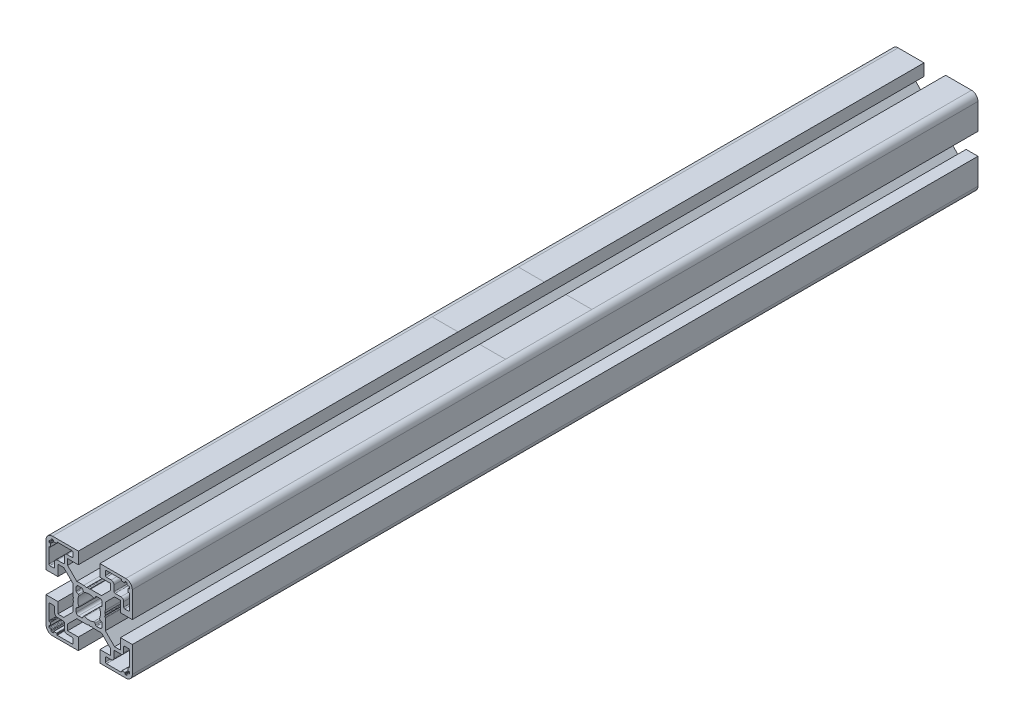
SolidWorks part; units mm, degrees
material "6063-T5"
ref_plane "Front Plane" through (0, 0, 0) normal (0, 0, 1) x (1, 0, 0)
ref_plane "Top Plane" through (0, 0, 0) normal (0, 1, 0) x (1, 0, 0)
ref_plane "Right Plane" through (0, 0, 0) normal (1, 0, 0) x (0, 0, -1)
ref_plane "Plan1" through (0, 0, 50) normal (0, 0, 1) x (1, 0, 0)
sketch "Esquisse1" plane through (0, 0, 50) normal (0, 0, 1) x (1, 0, 0)
  line L0 (-11.2645, -4.6769) -> (-11.2645, 2.1231)
  line L1 (-10.7645, 2.6231) -> (-9.0645, 2.6231)
  line L2 (-8.5645, 2.1231) -> (-8.5645, -0.0769)
  line L3 (-7.2645, -1.3769) -> (-4.5645, -1.3769)
  line L4 (-4.0645, -1.8769) -> (-4.0645, -4.5769)
  line L5 (-2.7645, -5.8769) -> (-0.5645, -5.8769)
  line L6 (-0.0645, -6.3769) -> (-0.0645, -8.0769)
  line L7 (-0.5645, -8.5769) -> (-7.3645, -8.5769)
  line L8 (-7.5645, -8.3769) -> (-7.5645, -8.0769)
  line L9 (-7.7645, -7.8769) -> (-8.9645, -7.8769)
  line L10 (-9.1645, -8.0769) -> (-9.1645, -8.3769)
  line L11 (-9.3645, -8.5769) -> (-9.8645, -8.5769)
  line L12 (-10.1645, -8.2769) -> (-10.1645, -7.7769)
  line L13 (-10.4645, -7.4769) -> (-10.9645, -7.4769)
  line L14 (-11.2645, -7.1769) -> (-11.2645, -6.6769)
  line L15 (-11.0645, -6.4769) -> (-10.7645, -6.4769)
  line L16 (-10.5645, -6.2769) -> (-10.5645, -5.0769)
  line L17 (-10.7645, -4.8769) -> (-11.0645, -4.8769)
  line L18 (14.9355, -8.0769) -> (14.9355, -6.3769)
  line L19 (15.4355, -5.8769) -> (17.6355, -5.8769)
  line L20 (18.9355, -4.5769) -> (18.9355, -1.8769)
  line L21 (19.4355, -1.3769) -> (22.1355, -1.3769)
  line L22 (23.4355, -0.0769) -> (23.4355, 2.1231)
  line L23 (23.9355, 2.6231) -> (25.6355, 2.6231)
  line L24 (26.1355, 2.1231) -> (26.1355, -4.6769)
  line L25 (25.9355, -4.8769) -> (25.6355, -4.8769)
  line L26 (25.4355, -5.0769) -> (25.4355, -6.2769)
  line L27 (25.6355, -6.4769) -> (25.9355, -6.4769)
  line L28 (26.1355, -6.6769) -> (26.1355, -7.1769)
  line L29 (25.8355, -7.4769) -> (25.3355, -7.4769)
  line L30 (25.0355, -7.7769) -> (25.0355, -8.2769)
  line L31 (24.7355, -8.5769) -> (24.2355, -8.5769)
  line L32 (24.0355, -8.3769) -> (24.0355, -8.0769)
  line L33 (23.8355, -7.8769) -> (22.6355, -7.8769)
  line L34 (22.4355, -8.0769) -> (22.4355, -8.3769)
  line L35 (22.2355, -8.5769) -> (15.4355, -8.5769)
  line L36 (-12.5645, 27.1231) -> (-12.5645, 15.1231)
  line L37 (-12.5645, 15.1231) -> (-7.0645, 15.1231)
  line L38 (-7.0645, 15.1231) -> (-7.0645, 20.1231)
  line L39 (-7.0645, 20.1231) -> (-4.3322, 20.1231)
  line L40 (-4.3322, 20.1231) -> (-0.0645, 15.8553)
  line L41 (-0.0645, 15.8553) -> (-0.0645, 10.7767)
  line L42 (0.0025, 10.5267) -> (0.2355, 10.1231)
  line L43 (0.2355, 10.1231) -> (0.0025, 9.7195)
  line L44 (0.0025, 9.2195) -> (0.1846, 8.9042)
  line L45 (0.1846, 8.9042) -> (-0.0645, 7.6231)
  line L46 (-0.0645, 7.6231) -> (-0.0645, 4.3908)
  line L47 (-0.0645, 4.3908) -> (-4.3322, 0.1231)
  line L48 (-4.3322, 0.1231) -> (-7.0645, 0.1231)
  line L49 (-7.0645, 0.1231) -> (-7.0645, 5.1231)
  line L50 (-7.0645, 5.1231) -> (-12.5645, 5.1231)
  line L51 (-12.5645, 5.1231) -> (-12.5645, -6.8769)
  line L52 (-9.5645, -9.8769) -> (2.4355, -9.8769)
  line L53 (2.4355, -9.8769) -> (2.4355, -4.3769)
  line L54 (2.4355, -4.3769) -> (-2.5645, -4.3769)
  line L55 (-2.5645, -4.3769) -> (-2.5645, -1.6447)
  line L56 (-2.5645, -1.6447) -> (1.7033, 2.6231)
  line L57 (1.7033, 2.6231) -> (6.7819, 2.6231)
  line L58 (7.0319, 2.6901) -> (7.4355, 2.9231)
  line L59 (7.4355, 2.9231) -> (7.8391, 2.6901)
  line L60 (8.3391, 2.6901) -> (8.6544, 2.8721)
  line L61 (8.6544, 2.8721) -> (9.9355, 2.6231)
  line L62 (9.9355, 2.6231) -> (13.1678, 2.6231)
  line L63 (13.1678, 2.6231) -> (17.4355, -1.6447)
  line L64 (17.4355, -1.6447) -> (17.4355, -4.3769)
  line L65 (17.4355, -4.3769) -> (12.4355, -4.3769)
  line L66 (12.4355, -4.3769) -> (12.4355, -9.8769)
  line L67 (12.4355, -9.8769) -> (24.4355, -9.8769)
  line L68 (27.4355, -6.8769) -> (27.4355, 5.1231)
  line L69 (27.4355, 5.1231) -> (21.9355, 5.1231)
  line L70 (21.9355, 5.1231) -> (21.9355, 0.1231)
  line L71 (21.9355, 0.1231) -> (19.2033, 0.1231)
  line L72 (19.2033, 0.1231) -> (14.9355, 4.3908)
  line L73 (14.9355, 4.3908) -> (14.9355, 9.4695)
  line L74 (14.8686, 9.7195) -> (14.6355, 10.1231)
  line L75 (14.6355, 10.1231) -> (14.8686, 10.5267)
  line L76 (14.8686, 11.0267) -> (14.6865, 11.342)
  line L77 (14.6865, 11.342) -> (14.9355, 12.6231)
  line L78 (14.9355, 12.6231) -> (14.9355, 15.8553)
  line L79 (14.9355, 15.8553) -> (19.2033, 20.1231)
  line L80 (19.2033, 20.1231) -> (21.9355, 20.1231)
  line L81 (21.9355, 20.1231) -> (21.9355, 15.1231)
  line L82 (21.9355, 15.1231) -> (27.4355, 15.1231)
  line L83 (27.4355, 15.1231) -> (27.4355, 27.1231)
  line L84 (24.4355, 30.1231) -> (12.4355, 30.1231)
  line L85 (12.4355, 30.1231) -> (12.4355, 24.6231)
  line L86 (12.4355, 24.6231) -> (17.4355, 24.6231)
  line L87 (17.4355, 24.6231) -> (17.4355, 21.8908)
  line L88 (17.4355, 21.8908) -> (13.1678, 17.6231)
  line L89 (13.1678, 17.6231) -> (8.0891, 17.6231)
  line L90 (7.8391, 17.5561) -> (7.4355, 17.3231)
  line L91 (7.4355, 17.3231) -> (7.0319, 17.5561)
  line L92 (6.5319, 17.5561) -> (6.2167, 17.3741)
  line L93 (6.2167, 17.3741) -> (4.9355, 17.6231)
  line L94 (4.9355, 17.6231) -> (1.7033, 17.6231)
  line L95 (1.7033, 17.6231) -> (-2.5645, 21.8908)
  line L96 (-2.5645, 21.8908) -> (-2.5645, 24.6231)
  line L97 (-2.5645, 24.6231) -> (2.4355, 24.6231)
  line L98 (2.4355, 24.6231) -> (2.4355, 30.1231)
  line L99 (2.4355, 30.1231) -> (-9.5645, 30.1231)
  line L100 (14.9355, 26.6231) -> (14.9355, 28.3231)
  line L101 (15.4355, 28.8231) -> (22.2355, 28.8231)
  line L102 (22.4355, 28.6231) -> (22.4355, 28.3231)
  line L103 (22.6355, 28.1231) -> (23.8355, 28.1231)
  line L104 (24.0355, 28.3231) -> (24.0355, 28.6231)
  line L105 (24.2355, 28.8231) -> (24.7355, 28.8231)
  line L106 (25.0355, 28.5231) -> (25.0355, 28.0231)
  line L107 (25.3355, 27.7231) -> (25.8355, 27.7231)
  line L108 (26.1355, 27.4231) -> (26.1355, 26.9231)
  line L109 (25.9355, 26.7231) -> (25.6355, 26.7231)
  line L110 (25.4355, 26.5231) -> (25.4355, 25.3231)
  line L111 (25.6355, 25.1231) -> (25.9355, 25.1231)
  line L112 (26.1355, 24.9231) -> (26.1355, 18.1231)
  line L113 (25.6355, 17.6231) -> (23.9355, 17.6231)
  line L114 (23.4355, 18.1231) -> (23.4355, 20.3231)
  line L115 (22.1355, 21.6231) -> (19.4355, 21.6231)
  line L116 (18.9355, 22.1231) -> (18.9355, 24.8231)
  line L117 (17.6355, 26.1231) -> (15.4355, 26.1231)
  line L118 (-11.2645, 18.1231) -> (-11.2645, 24.9231)
  line L119 (-11.0645, 25.1231) -> (-10.7645, 25.1231)
  line L120 (-10.5645, 25.3231) -> (-10.5645, 26.5231)
  line L121 (-10.7645, 26.7231) -> (-11.0645, 26.7231)
  line L122 (-11.2645, 26.9231) -> (-11.2645, 27.4231)
  line L123 (-10.9645, 27.7231) -> (-10.4645, 27.7231)
  line L124 (-10.1645, 28.0231) -> (-10.1645, 28.5231)
  line L125 (-9.8645, 28.8231) -> (-9.3645, 28.8231)
  line L126 (-9.1645, 28.6231) -> (-9.1645, 28.3231)
  line L127 (-8.9645, 28.1231) -> (-7.7645, 28.1231)
  line L128 (-7.5645, 28.3231) -> (-7.5645, 28.6231)
  line L129 (-7.3645, 28.8231) -> (-0.5645, 28.8231)
  line L130 (-0.0645, 28.3231) -> (-0.0645, 26.6231)
  line L131 (-0.5645, 26.1231) -> (-2.7645, 26.1231)
  line L132 (-4.0645, 24.8231) -> (-4.0645, 22.1231)
  line L133 (-4.5645, 21.6231) -> (-7.2645, 21.6231)
  line L134 (-8.5645, 20.3231) -> (-8.5645, 18.1231)
  line L135 (-9.0645, 17.6231) -> (-10.7645, 17.6231)
  line L136 (10.9262, 16.1231) -> (12.4355, 16.1231)
  line L137 (13.4355, 15.1231) -> (13.4355, 13.6138)
  line L138 (13.1703, 13.1723) -> (12.4933, 12.8123)
  line L139 (12.4933, 7.4338) -> (13.1703, 7.0739)
  line L140 (13.4355, 6.6324) -> (13.4355, 5.1231)
  line L141 (12.4355, 4.1231) -> (10.9262, 4.1231)
  line L142 (10.4848, 4.3883) -> (10.1248, 5.0654)
  line L143 (4.7463, 5.0654) -> (4.3863, 4.3883)
  line L144 (3.9449, 4.1231) -> (2.4355, 4.1231)
  line L145 (1.4355, 5.1231) -> (1.4355, 6.6324)
  line L146 (1.7008, 7.0739) -> (2.3778, 7.4338)
  line L147 (2.3778, 12.8123) -> (1.7008, 13.1723)
  line L148 (1.4355, 13.6138) -> (1.4355, 15.1231)
  line L149 (2.4355, 16.1231) -> (3.9449, 16.1231)
  line L150 (4.3863, 15.8578) -> (4.7463, 15.1808)
  line L151 (10.1248, 15.1808) -> (10.4848, 15.8578)
  arc A0 (-11.2645, 2.1231) -> (-10.7645, 2.6231) centre (-10.7645, 2.1231) cw
  arc A1 (-9.0645, 2.6231) -> (-8.5645, 2.1231) centre (-9.0645, 2.1231) cw
  arc A2 (-8.5645, -0.0769) -> (-7.2645, -1.3769) centre (-7.2645, -0.0769) ccw
  arc A3 (-4.5645, -1.3769) -> (-4.0645, -1.8769) centre (-4.5645, -1.8769) cw
  arc A4 (-4.0645, -4.5769) -> (-2.7645, -5.8769) centre (-2.7645, -4.5769) ccw
  arc A5 (-0.5645, -5.8769) -> (-0.0645, -6.3769) centre (-0.5645, -6.3769) cw
  arc A6 (-0.0645, -8.0769) -> (-0.5645, -8.5769) centre (-0.5645, -8.0769) cw
  arc A7 (-7.3645, -8.5769) -> (-7.5645, -8.3769) centre (-7.3645, -8.3769) cw
  arc A8 (-7.5645, -8.0769) -> (-7.7645, -7.8769) centre (-7.7645, -8.0769) ccw
  arc A9 (-8.9645, -7.8769) -> (-9.1645, -8.0769) centre (-8.9645, -8.0769) ccw
  arc A10 (-9.1645, -8.3769) -> (-9.3645, -8.5769) centre (-9.3645, -8.3769) cw
  arc A11 (-9.8645, -8.5769) -> (-10.1645, -8.2769) centre (-9.8645, -8.2769) cw
  arc A12 (-10.1645, -7.7769) -> (-10.4645, -7.4769) centre (-10.4645, -7.7769) ccw
  arc A13 (-10.9645, -7.4769) -> (-11.2645, -7.1769) centre (-10.9645, -7.1769) cw
  arc A14 (-11.2645, -6.6769) -> (-11.0645, -6.4769) centre (-11.0645, -6.6769) cw
  arc A15 (-10.7645, -6.4769) -> (-10.5645, -6.2769) centre (-10.7645, -6.2769) ccw
  arc A16 (-10.5645, -5.0769) -> (-10.7645, -4.8769) centre (-10.7645, -5.0769) ccw
  arc A17 (-11.0645, -4.8769) -> (-11.2645, -4.6769) centre (-11.0645, -4.6769) cw
  arc A18 (14.9355, -6.3769) -> (15.4355, -5.8769) centre (15.4355, -6.3769) cw
  arc A19 (17.6355, -5.8769) -> (18.9355, -4.5769) centre (17.6355, -4.5769) ccw
  arc A20 (18.9355, -1.8769) -> (19.4355, -1.3769) centre (19.4355, -1.8769) cw
  arc A21 (22.1355, -1.3769) -> (23.4355, -0.0769) centre (22.1355, -0.0769) ccw
  arc A22 (23.4355, 2.1231) -> (23.9355, 2.6231) centre (23.9355, 2.1231) cw
  arc A23 (25.6355, 2.6231) -> (26.1355, 2.1231) centre (25.6355, 2.1231) cw
  arc A24 (26.1355, -4.6769) -> (25.9355, -4.8769) centre (25.9355, -4.6769) cw
  arc A25 (25.6355, -4.8769) -> (25.4355, -5.0769) centre (25.6355, -5.0769) ccw
  arc A26 (25.4355, -6.2769) -> (25.6355, -6.4769) centre (25.6355, -6.2769) ccw
  arc A27 (25.9355, -6.4769) -> (26.1355, -6.6769) centre (25.9355, -6.6769) cw
  arc A28 (26.1355, -7.1769) -> (25.8355, -7.4769) centre (25.8355, -7.1769) cw
  arc A29 (25.3355, -7.4769) -> (25.0355, -7.7769) centre (25.3355, -7.7769) ccw
  arc A30 (25.0355, -8.2769) -> (24.7355, -8.5769) centre (24.7355, -8.2769) cw
  arc A31 (24.2355, -8.5769) -> (24.0355, -8.3769) centre (24.2355, -8.3769) cw
  arc A32 (24.0355, -8.0769) -> (23.8355, -7.8769) centre (23.8355, -8.0769) ccw
  arc A33 (22.6355, -7.8769) -> (22.4355, -8.0769) centre (22.6355, -8.0769) ccw
  arc A34 (22.4355, -8.3769) -> (22.2355, -8.5769) centre (22.2355, -8.3769) cw
  arc A35 (15.4355, -8.5769) -> (14.9355, -8.0769) centre (15.4355, -8.0769) cw
  arc A36 (-9.5645, 30.1231) -> (-12.5645, 27.1231) centre (-9.5645, 27.1231) ccw
  arc A37 (-0.0645, 10.7767) -> (0.0025, 10.5267) centre (0.4355, 10.7767) ccw
  arc A38 (0.0025, 9.7195) -> (0.0025, 9.2195) centre (0.4355, 9.4695) ccw
  arc A39 (-12.5645, -6.8769) -> (-9.5645, -9.8769) centre (-9.5645, -6.8769) ccw
  arc A40 (6.7819, 2.6231) -> (7.0319, 2.6901) centre (6.7819, 3.1231) ccw
  arc A41 (7.8391, 2.6901) -> (8.3391, 2.6901) centre (8.0891, 3.1231) ccw
  arc A42 (24.4355, -9.8769) -> (27.4355, -6.8769) centre (24.4355, -6.8769) ccw
  arc A43 (14.9355, 9.4695) -> (14.8686, 9.7195) centre (14.4355, 9.4695) ccw
  arc A44 (14.8686, 10.5267) -> (14.8686, 11.0267) centre (14.4355, 10.7767) ccw
  arc A45 (27.4355, 27.1231) -> (24.4355, 30.1231) centre (24.4355, 27.1231) ccw
  arc A46 (8.0891, 17.6231) -> (7.8391, 17.5561) centre (8.0891, 17.1231) ccw
  arc A47 (7.0319, 17.5561) -> (6.5319, 17.5561) centre (6.7819, 17.1231) ccw
  arc A48 (14.9355, 28.3231) -> (15.4355, 28.8231) centre (15.4355, 28.3231) cw
  arc A49 (22.2355, 28.8231) -> (22.4355, 28.6231) centre (22.2355, 28.6231) cw
  arc A50 (22.4355, 28.3231) -> (22.6355, 28.1231) centre (22.6355, 28.3231) ccw
  arc A51 (23.8355, 28.1231) -> (24.0355, 28.3231) centre (23.8355, 28.3231) ccw
  arc A52 (24.0355, 28.6231) -> (24.2355, 28.8231) centre (24.2355, 28.6231) cw
  arc A53 (24.7355, 28.8231) -> (25.0355, 28.5231) centre (24.7355, 28.5231) cw
  arc A54 (25.0355, 28.0231) -> (25.3355, 27.7231) centre (25.3355, 28.0231) ccw
  arc A55 (25.8355, 27.7231) -> (26.1355, 27.4231) centre (25.8355, 27.4231) cw
  arc A56 (26.1355, 26.9231) -> (25.9355, 26.7231) centre (25.9355, 26.9231) cw
  arc A57 (25.6355, 26.7231) -> (25.4355, 26.5231) centre (25.6355, 26.5231) ccw
  arc A58 (25.4355, 25.3231) -> (25.6355, 25.1231) centre (25.6355, 25.3231) ccw
  arc A59 (25.9355, 25.1231) -> (26.1355, 24.9231) centre (25.9355, 24.9231) cw
  arc A60 (26.1355, 18.1231) -> (25.6355, 17.6231) centre (25.6355, 18.1231) cw
  arc A61 (23.9355, 17.6231) -> (23.4355, 18.1231) centre (23.9355, 18.1231) cw
  arc A62 (23.4355, 20.3231) -> (22.1355, 21.6231) centre (22.1355, 20.3231) ccw
  arc A63 (19.4355, 21.6231) -> (18.9355, 22.1231) centre (19.4355, 22.1231) cw
  arc A64 (18.9355, 24.8231) -> (17.6355, 26.1231) centre (17.6355, 24.8231) ccw
  arc A65 (15.4355, 26.1231) -> (14.9355, 26.6231) centre (15.4355, 26.6231) cw
  arc A66 (-11.2645, 24.9231) -> (-11.0645, 25.1231) centre (-11.0645, 24.9231) cw
  arc A67 (-10.7645, 25.1231) -> (-10.5645, 25.3231) centre (-10.7645, 25.3231) ccw
  arc A68 (-10.5645, 26.5231) -> (-10.7645, 26.7231) centre (-10.7645, 26.5231) ccw
  arc A69 (-11.0645, 26.7231) -> (-11.2645, 26.9231) centre (-11.0645, 26.9231) cw
  arc A70 (-11.2645, 27.4231) -> (-10.9645, 27.7231) centre (-10.9645, 27.4231) cw
  arc A71 (-10.4645, 27.7231) -> (-10.1645, 28.0231) centre (-10.4645, 28.0231) ccw
  arc A72 (-10.1645, 28.5231) -> (-9.8645, 28.8231) centre (-9.8645, 28.5231) cw
  arc A73 (-9.3645, 28.8231) -> (-9.1645, 28.6231) centre (-9.3645, 28.6231) cw
  arc A74 (-9.1645, 28.3231) -> (-8.9645, 28.1231) centre (-8.9645, 28.3231) ccw
  arc A75 (-7.7645, 28.1231) -> (-7.5645, 28.3231) centre (-7.7645, 28.3231) ccw
  arc A76 (-7.5645, 28.6231) -> (-7.3645, 28.8231) centre (-7.3645, 28.6231) cw
  arc A77 (-0.5645, 28.8231) -> (-0.0645, 28.3231) centre (-0.5645, 28.3231) cw
  arc A78 (-0.0645, 26.6231) -> (-0.5645, 26.1231) centre (-0.5645, 26.6231) cw
  arc A79 (-2.7645, 26.1231) -> (-4.0645, 24.8231) centre (-2.7645, 24.8231) ccw
  arc A80 (-4.0645, 22.1231) -> (-4.5645, 21.6231) centre (-4.5645, 22.1231) cw
  arc A81 (-7.2645, 21.6231) -> (-8.5645, 20.3231) centre (-7.2645, 20.3231) ccw
  arc A82 (-8.5645, 18.1231) -> (-9.0645, 17.6231) centre (-9.0645, 18.1231) cw
  arc A83 (-10.7645, 17.6231) -> (-11.2645, 18.1231) centre (-10.7645, 18.1231) cw
  arc A84 (12.4355, 16.1231) -> (13.4355, 15.1231) centre (12.4355, 15.1231) cw
  arc A85 (13.4355, 13.6138) -> (13.1703, 13.1723) centre (12.9355, 13.6138) cw
  arc A86 (12.4933, 12.8123) -> (12.2678, 12.1754) centre (12.728, 12.3708) ccw
  arc A87 (12.2678, 12.1754) -> (12.2678, 8.0708) centre (7.4355, 10.1231) cw
  arc A88 (12.2678, 8.0708) -> (12.4933, 7.4338) centre (12.728, 7.8753) ccw
  arc A89 (13.1703, 7.0739) -> (13.4355, 6.6324) centre (12.9355, 6.6324) cw
  arc A90 (13.4355, 5.1231) -> (12.4355, 4.1231) centre (12.4355, 5.1231) cw
  arc A91 (10.9262, 4.1231) -> (10.4848, 4.3883) centre (10.9262, 4.6231) cw
  arc A92 (10.1248, 5.0654) -> (9.4878, 5.2908) centre (9.6833, 4.8306) ccw
  arc A93 (9.4878, 5.2908) -> (5.3832, 5.2908) centre (7.4355, 10.1231) cw
  arc A94 (5.3832, 5.2908) -> (4.7463, 5.0654) centre (5.1878, 4.8306) ccw
  arc A95 (4.3863, 4.3883) -> (3.9449, 4.1231) centre (3.9449, 4.6231) cw
  arc A96 (2.4355, 4.1231) -> (1.4355, 5.1231) centre (2.4355, 5.1231) cw
  arc A97 (1.4355, 6.6324) -> (1.7008, 7.0739) centre (1.9355, 6.6324) cw
  arc A98 (2.3778, 7.4338) -> (2.6033, 8.0708) centre (2.1431, 7.8753) ccw
  arc A99 (2.6033, 8.0708) -> (2.6033, 12.1754) centre (7.4355, 10.1231) cw
  arc A100 (2.6033, 12.1754) -> (2.3778, 12.8123) centre (2.1431, 12.3708) ccw
  arc A101 (1.7008, 13.1723) -> (1.4355, 13.6138) centre (1.9355, 13.6138) cw
  arc A102 (1.4355, 15.1231) -> (2.4355, 16.1231) centre (2.4355, 15.1231) cw
  arc A103 (3.9449, 16.1231) -> (4.3863, 15.8578) centre (3.9449, 15.6231) cw
  arc A104 (4.7463, 15.1808) -> (5.3832, 14.9553) centre (5.1878, 15.4155) ccw
  arc A105 (5.3832, 14.9553) -> (9.4878, 14.9553) centre (7.4355, 10.1231) cw
  arc A106 (9.4878, 14.9553) -> (10.1248, 15.1808) centre (9.6833, 15.4155) ccw
  arc A107 (10.4848, 15.8578) -> (10.9262, 16.1231) centre (10.9262, 15.6231) cw
extrude "Boss.-Extru.1" add sketch "Esquisse1" against normal blind 392
sketch "Esquisse2" plane through (0, 30.1231, 0) normal (0, 1, 0) x (1, 0, 0)
  line L0 (-12.5645, 342) -> (-12.5645, -50) construction
  line L1 (-12.5645, 166) -> (27.4355, 166)
  line L2 (-12.5645, 166) -> (-12.5645, 126)
  line L3 (-12.5645, 126) -> (27.4355, 126)
  line L4 (27.4355, 166) -> (27.4355, 126)
  line L5 (27.4355, 342) -> (27.4355, -50) construction
  line L6 (-12.5645, 146) -> (27.4355, 146) construction
  dimension "D1" = 40
split line "Ligne de séparation1"
